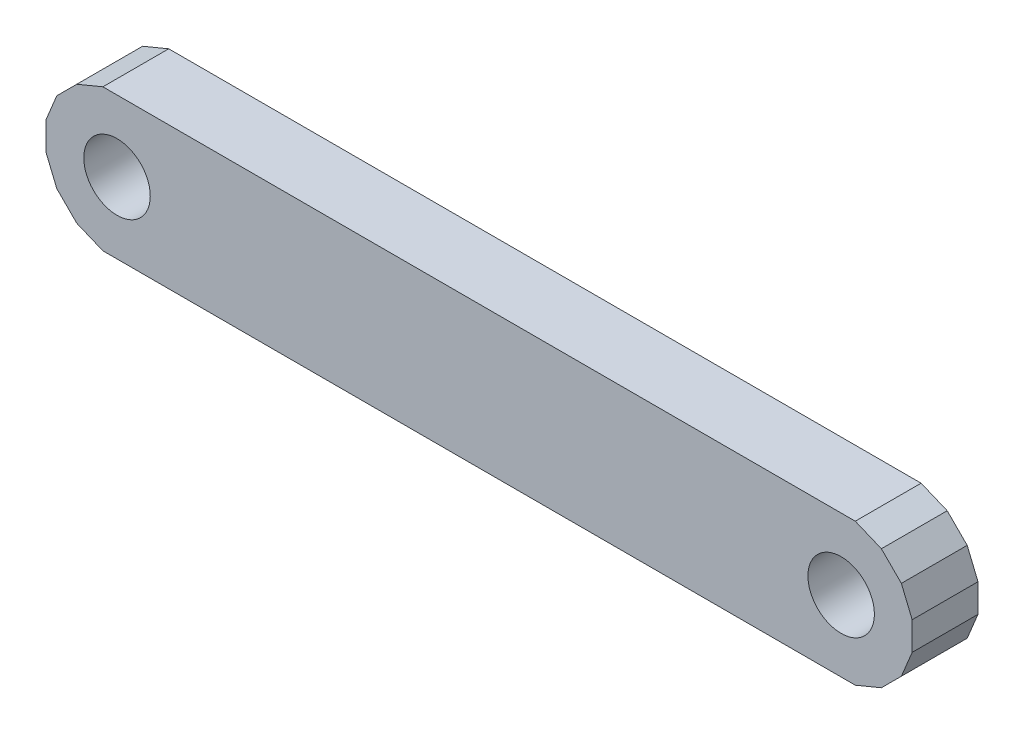
SolidWorks part; units mm, degrees
ref_plane "前视基准面" through (0, 0, 0) normal (0, 0, 1) x (1, 0, 0)
ref_plane "上视基准面" through (0, 0, 0) normal (0, 1, 0) x (1, 0, 0)
ref_plane "右视基准面" through (0, 0, 0) normal (1, 0, 0) x (0, 0, -1)
other "Configuration Table"
sketch "Profile_1" plane through (0, 0, 0) normal (0, 0, 1) x (1, 0, 0)
  line L0 (9.1462, 6.1113) -> (6.1113, 9.1462)
  line L1 (6.1113, 9.1462) -> (2.146, 10.7886)
  line L2 (2.146, 10.7886) -> (-112.146, 10.7886)
  line L3 (-112.146, 10.7886) -> (-116.1113, 9.1462)
  line L4 (-116.1113, 9.1462) -> (-119.1462, 6.1113)
  line L5 (-119.1462, 6.1113) -> (-120.7886, 2.146)
  line L6 (-120.7886, 2.146) -> (-120.7886, -2.146)
  line L7 (-120.7886, -2.146) -> (-119.1462, -6.1113)
  line L8 (-119.1462, -6.1113) -> (-116.1113, -9.1462)
  line L9 (-116.1113, -9.1462) -> (-112.146, -10.7886)
  line L10 (-112.146, -10.7886) -> (2.146, -10.7886)
  line L11 (2.146, -10.7886) -> (6.1113, -9.1462)
  line L12 (6.1113, -9.1462) -> (9.1462, -6.1113)
  line L13 (9.1462, -6.1113) -> (10.7886, -2.146)
  line L14 (10.7886, -2.146) -> (10.7886, 2.146)
  line L15 (10.7886, 2.146) -> (9.1462, 6.1113)
  circle A0 centre (0, 0) radius 5.05
  circle A1 centre (-110, 0) radius 5.05
extrude "Passive_arm" add sketch "Profile_1" along normal blind 10 from offset 8
